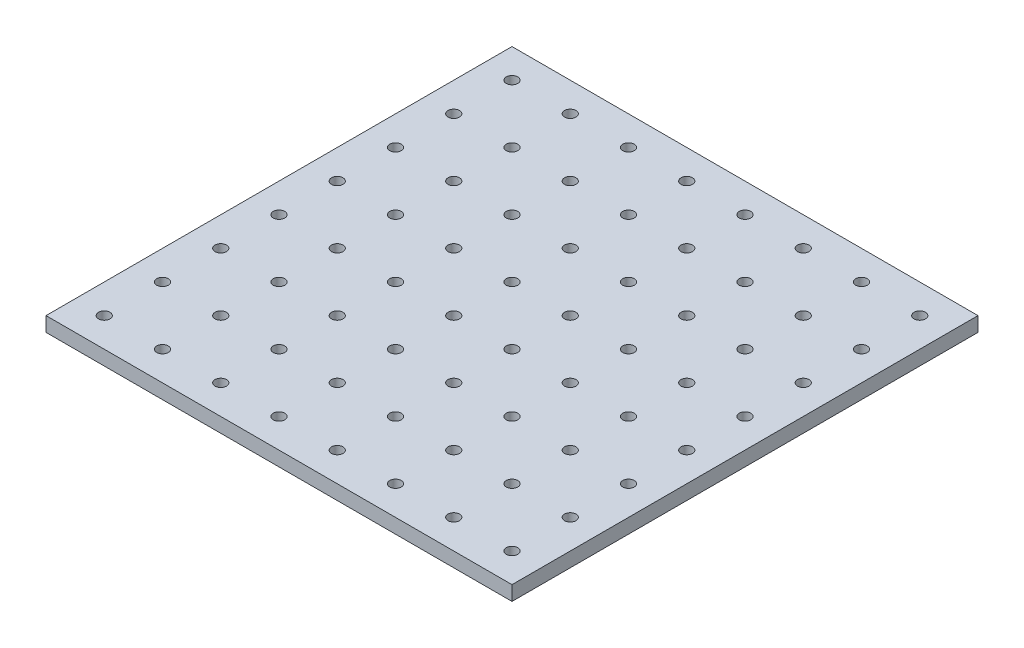
SolidWorks part; units mm, degrees
ref_plane "Front Plane" through (0, 0, 0) normal (0, 0, 1) x (1, 0, 0)
ref_plane "Top Plane" through (0, 0, 0) normal (0, 1, 0) x (1, 0, 0)
ref_plane "Right Plane" through (0, 0, 0) normal (1, 0, 0) x (0, 0, -1)
sketch "Sketch1" plane through (0, 0, 0) normal (0, 1, 0) x (1, 0, 0)
  line L1 (-127, 127) -> (76.2, 127)
  line L2 (-127, 127) -> (-127, -76.2)
  line L3 (-127, -76.2) -> (76.2, -76.2)
  line L4 (76.2, 127) -> (76.2, -76.2)
  line L5 (-127, 127) -> (76.2, -76.2) construction
  line L6 (-127, -76.2) -> (76.2, 127) construction
  circle A0 centre (-114.3, 114.3) radius 2.5
  circle A1 centre (-88.9, 114.3) radius 2.5
  circle A2 centre (-63.5, 114.3) radius 2.5
  circle A3 centre (-38.1, 114.3) radius 2.5
  circle A4 centre (-12.7, 114.3) radius 2.5
  circle A5 centre (12.7, 114.3) radius 2.5
  circle A6 centre (38.1, 114.3) radius 2.5
  circle A7 centre (63.5, 114.3) radius 2.5
  circle A10 centre (-88.9, 88.9) radius 2.5
  circle A11 centre (-63.5, 88.9) radius 2.5
  circle A12 centre (-38.1, 88.9) radius 2.5
  circle A13 centre (-12.7, 88.9) radius 2.5
  circle A14 centre (12.7, 88.9) radius 2.5
  circle A15 centre (38.1, 88.9) radius 2.5
  circle A16 centre (63.5, 88.9) radius 2.5
  circle A19 centre (-88.9, 63.5) radius 2.5
  circle A20 centre (-63.5, 63.5) radius 2.5
  circle A21 centre (-38.1, 63.5) radius 2.5
  circle A22 centre (-12.7, 63.5) radius 2.5
  circle A23 centre (12.7, 63.5) radius 2.5
  circle A24 centre (38.1, 63.5) radius 2.5
  circle A25 centre (63.5, 63.5) radius 2.5
  circle A28 centre (-88.9, 38.1) radius 2.5
  circle A29 centre (-63.5, 38.1) radius 2.5
  circle A30 centre (-38.1, 38.1) radius 2.5
  circle A31 centre (-12.7, 38.1) radius 2.5
  circle A32 centre (12.7, 38.1) radius 2.5
  circle A33 centre (38.1, 38.1) radius 2.5
  circle A34 centre (63.5, 38.1) radius 2.5
  circle A37 centre (-88.9, 12.7) radius 2.5
  circle A38 centre (-63.5, 12.7) radius 2.5
  circle A39 centre (-38.1, 12.7) radius 2.5
  circle A40 centre (-12.7, 12.7) radius 2.5
  circle A41 centre (12.7, 12.7) radius 2.5
  circle A42 centre (38.1, 12.7) radius 2.5
  circle A43 centre (63.5, 12.7) radius 2.5
  circle A46 centre (-88.9, -12.7) radius 2.5
  circle A47 centre (-63.5, -12.7) radius 2.5
  circle A48 centre (-38.1, -12.7) radius 2.5
  circle A49 centre (-12.7, -12.7) radius 2.5
  circle A50 centre (12.7, -12.7) radius 2.5
  circle A51 centre (38.1, -12.7) radius 2.5
  circle A52 centre (63.5, -12.7) radius 2.5
  circle A55 centre (-88.9, -38.1) radius 2.5
  circle A56 centre (-63.5, -38.1) radius 2.5
  circle A57 centre (-38.1, -38.1) radius 2.5
  circle A58 centre (-12.7, -38.1) radius 2.5
  circle A59 centre (12.7, -38.1) radius 2.5
  circle A60 centre (38.1, -38.1) radius 2.5
  circle A61 centre (63.5, -38.1) radius 2.5
  circle A64 centre (-88.9, -63.5) radius 2.5
  circle A65 centre (-63.5, -63.5) radius 2.5
  circle A66 centre (-38.1, -63.5) radius 2.5
  circle A67 centre (-12.7, -63.5) radius 2.5
  circle A68 centre (12.7, -63.5) radius 2.5
  circle A69 centre (38.1, -63.5) radius 2.5
  circle A70 centre (63.5, -63.5) radius 2.5
  circle A91 centre (-114.3, 88.9) radius 2.5
  circle A92 centre (-114.3, 63.5) radius 2.5
  circle A93 centre (-114.3, 38.1) radius 2.5
  circle A94 centre (-114.3, 12.7) radius 2.5
  circle A95 centre (-114.3, -12.7) radius 2.5
  circle A96 centre (-114.3, -38.1) radius 2.5
  circle A97 centre (-114.3, -63.5) radius 2.5
  circle A100 centre (88.9, 114.3) radius 2.5 [skipped]
  circle A101 centre (114.3, 114.3) radius 2.5 [skipped]
  circle A102 centre (88.9, 88.9) radius 2.5 [skipped]
  circle A103 centre (114.3, 88.9) radius 2.5 [skipped]
  circle A104 centre (88.9, 63.5) radius 2.5 [skipped]
  circle A105 centre (114.3, 63.5) radius 2.5 [skipped]
  circle A106 centre (88.9, 38.1) radius 2.5 [skipped]
  circle A107 centre (114.3, 38.1) radius 2.5 [skipped]
  circle A108 centre (88.9, 12.7) radius 2.5 [skipped]
  circle A109 centre (114.3, 12.7) radius 2.5 [skipped]
  circle A110 centre (88.9, -12.7) radius 2.5 [skipped]
  circle A111 centre (114.3, -12.7) radius 2.5 [skipped]
  circle A112 centre (88.9, -38.1) radius 2.5 [skipped]
  circle A113 centre (114.3, -38.1) radius 2.5 [skipped]
  circle A114 centre (88.9, -63.5) radius 2.5 [skipped]
  circle A115 centre (114.3, -63.5) radius 2.5 [skipped]
  circle A116 centre (88.9, -88.9) radius 2.5 [skipped]
  circle A117 centre (114.3, -88.9) radius 2.5 [skipped]
  circle A118 centre (88.9, -114.3) radius 2.5 [skipped]
  circle A119 centre (114.3, -114.3) radius 2.5 [skipped]
  circle A120 centre (-88.9, -88.9) radius 2.5 [skipped]
  circle A121 centre (-63.5, -88.9) radius 2.5 [skipped]
  circle A122 centre (-38.1, -88.9) radius 2.5 [skipped]
  circle A123 centre (-12.7, -88.9) radius 2.5 [skipped]
  circle A124 centre (12.7, -88.9) radius 2.5 [skipped]
  circle A125 centre (38.1, -88.9) radius 2.5 [skipped]
  circle A126 centre (63.5, -88.9) radius 2.5 [skipped]
  circle A127 centre (-88.9, -114.3) radius 2.5 [skipped]
  circle A128 centre (-63.5, -114.3) radius 2.5 [skipped]
  circle A129 centre (-38.1, -114.3) radius 2.5 [skipped]
  circle A130 centre (-12.7, -114.3) radius 2.5 [skipped]
  circle A131 centre (12.7, -114.3) radius 2.5 [skipped]
  circle A132 centre (38.1, -114.3) radius 2.5 [skipped]
  circle A133 centre (63.5, -114.3) radius 2.5 [skipped]
  circle A134 centre (-114.3, -88.9) radius 2.5 [skipped]
  circle A135 centre (-114.3, -114.3) radius 2.5 [skipped]
  dimension "D5" = 10
  dimension "D1" = 12.7
  dimension "D2" = 203.2
  dimension "D3" = 12.7
  dimension "D4" = 203.2
extrude "Boss-Extrude1" add sketch "Sketch1" along normal blind 6.35
